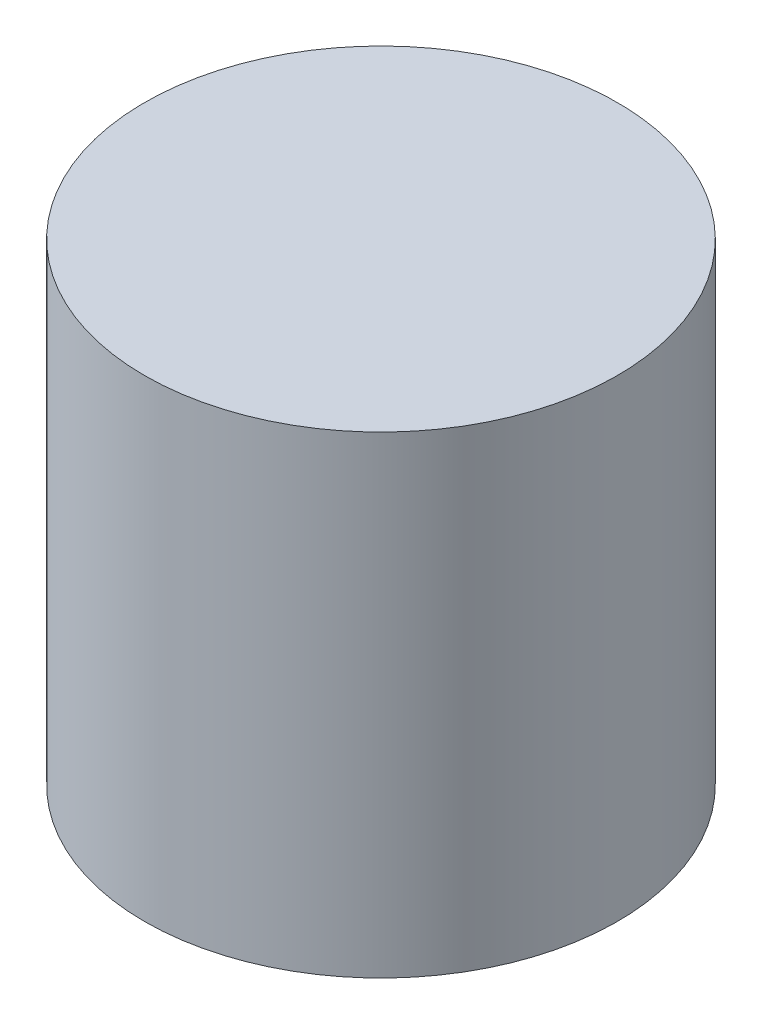
SolidWorks part; units mm, degrees
ref_plane "Front Plane" through (0, 0, 0) normal (0, 0, 1) x (1, 0, 0)
ref_plane "Top Plane" through (0, 0, 0) normal (0, 1, 0) x (1, 0, 0)
ref_plane "Right Plane" through (0, 0, 0) normal (1, 0, 0) x (0, 0, -1)
sketch "Sketch1" plane through (0, 0, 0) normal (0, 1, 0) x (1, 0, 0)
  circle A0 centre (0, 0) radius 3
  dimension "D1" = 6
extrude "Boss-Extrude1" add sketch "Sketch1" along normal mid plane 6
